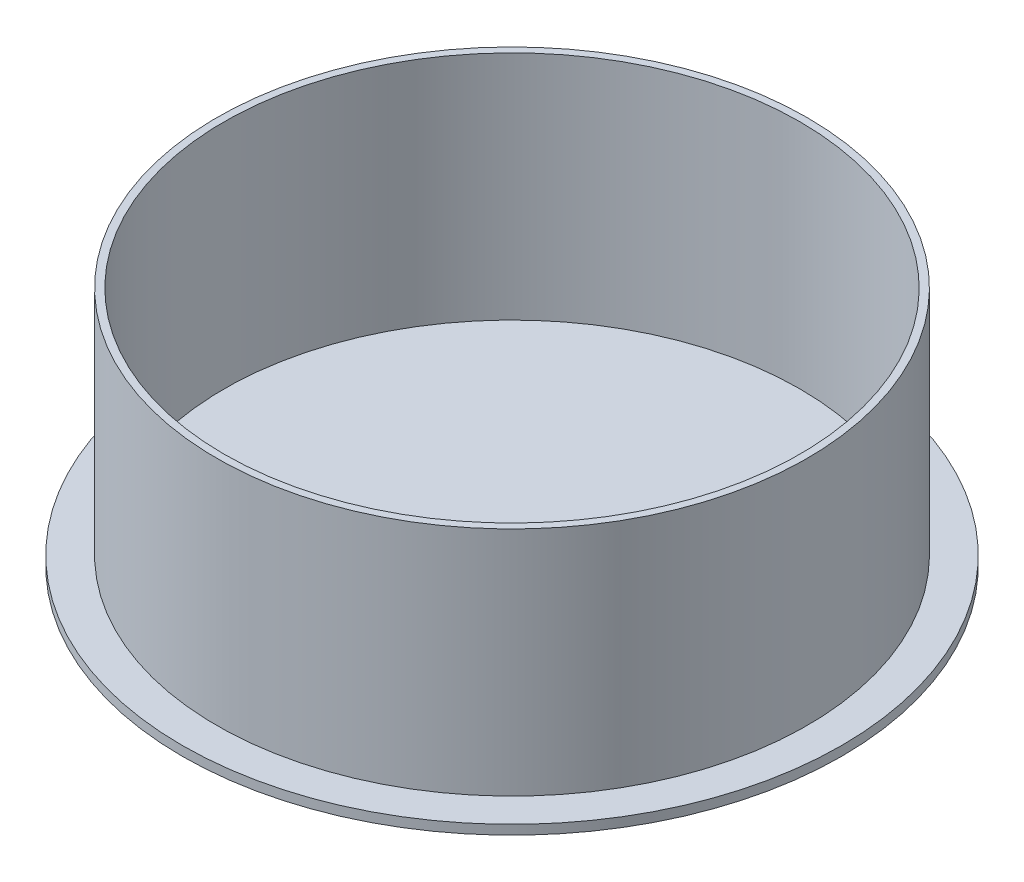
SolidWorks part; units mm, degrees
material "PVC Rígido"
ref_plane "Alzado" through (0, 0, 0) normal (0, 0, 1) x (1, 0, 0)
ref_plane "Planta" through (0, 0, 0) normal (0, 1, 0) x (1, 0, 0)
ref_plane "Vista lateral" through (0, 0, 0) normal (1, 0, 0) x (0, 0, -1)
sketch "Croquis1" plane through (0, 0, 0) normal (0, 0, 1) x (1, 0, 0)
  line L3 (-77.724, 62.46) -> (-77.724, 0)
  line L6 (0, 0) -> (0, 246.9754) construction
  line L9 (-77.724, 62.46) -> (-79.6798, 62.46)
  line L11 (-79.6798, 62.46) -> (-79.6798, 0)
  line L12 (-79.6798, 0) -> (-89, 0)
  line L13 (-89, 0) -> (-89, -2.54)
  line L14 (-89, -2.54) -> (0, -2.54)
  line L15 (0, -2.54) -> (0, 0)
  line L16 (0, 0) -> (-77.724, 0)
  dimension "D1" = 155.448
  dimension "D2" = 1.9558
  dimension "D3" = 2.54
  dimension "D4" = 178
  dimension "D5" = 65
revolve "Revolución1" add sketch "Croquis1" angle 360 about L6
